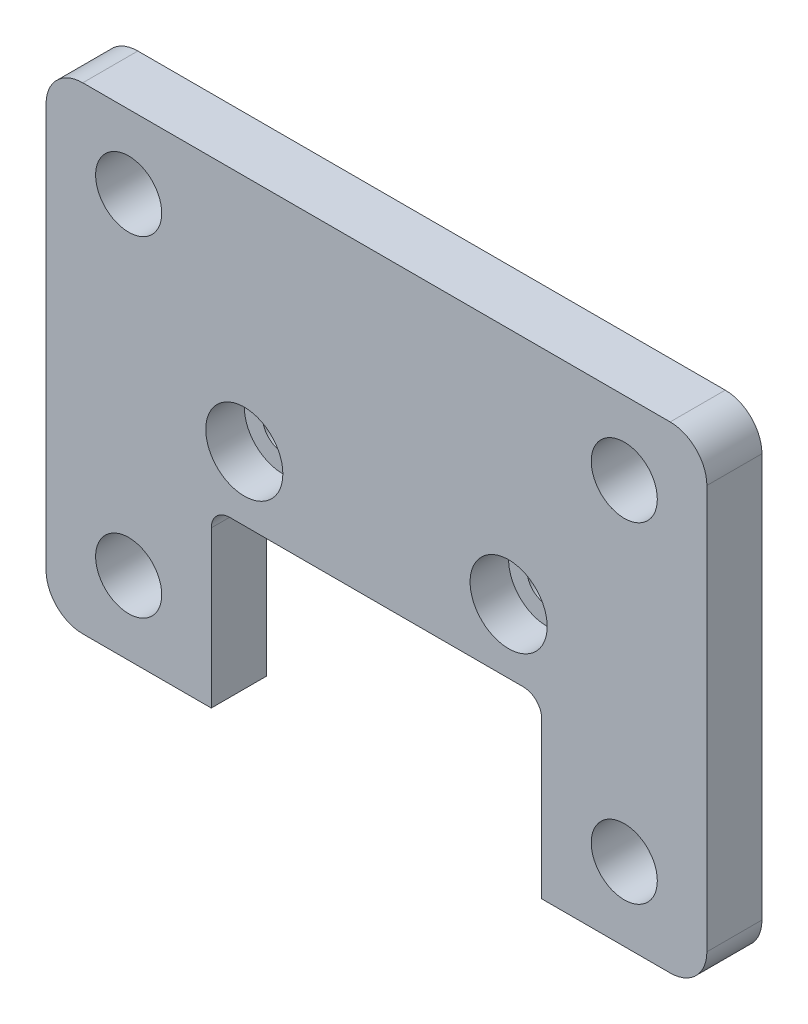
SolidWorks part; units mm, degrees
ref_plane "前视基准面" through (0, 0, 0) normal (0, 0, 1) x (1, 0, 0)
ref_plane "上视基准面" through (0, 0, 0) normal (0, 1, 0) x (1, 0, 0)
ref_plane "右视基准面" through (0, 0, 0) normal (1, 0, 0) x (0, 0, -1)
sketch "草图1" plane through (0, 0, 0) normal (0, 0, 1) x (1, 0, 0)
  line L0 (-16, -13) -> (16, -13)
  line L1 (18, -11) -> (18, 11)
  line L2 (16, 13) -> (-16, 13)
  line L3 (-18, 11) -> (-18, -11)
  arc A0 (16, -13) -> (18, -11) centre (16, -11) ccw
  arc A1 (18, 11) -> (16, 13) centre (16, 11) ccw
  arc A2 (-16, 13) -> (-18, 11) centre (-16, 11) ccw
  arc A3 (-18, -11) -> (-16, -13) centre (-16, -11) ccw
  dimension "D1" = 2
  dimension "D2" = 18
  dimension "D3" = 18
  dimension "D4" = 13
  dimension "D5" = 13
extrude "背板拉伸_厚3_前面Z5" add sketch "草图1" along normal blind 3 from offset 5
sketch "草图2" plane through (0, 0, 0) normal (0, 0, 1) x (1, 0, 0)
  line L0 (-8, -20) -> (8, -20)
  line L1 (9, -19) -> (9, -4.5)
  line L2 (8, -3.5) -> (-8, -3.5)
  line L3 (-9, -4.5) -> (-9, -19)
  arc A0 (8, -20) -> (9, -19) centre (8, -19) ccw
  arc A1 (9, -4.5) -> (8, -3.5) centre (8, -4.5) ccw
  arc A2 (-8, -3.5) -> (-9, -4.5) centre (-8, -4.5) ccw
  arc A3 (-9, -19) -> (-8, -20) centre (-8, -19) ccw
  dimension "D1" = 1
  dimension "D2" = 9
  dimension "D3" = 9
  dimension "D4" = 3.5
  dimension "D5" = 20
extrude "下方U口_宽18_向下敞开" cut sketch "草图2" along normal blind 3 from offset 5
sketch "草图3" plane through (0, 0, 0) normal (0, 0, 1) x (1, 0, 0)
  circle A0 centre (-7.2, 0) radius 2.75
  circle A1 centre (7.2, 0) radius 2.75
  dimension "D1" = 5.5
  dimension "D2" = 7.2
  dimension "D3" = 7.2
extrude "两根支柱主体_高2_Z3至5" add sketch "草图3" along normal blind 2 from offset 3
sketch "草图4" plane through (0, 0, 0) normal (0, 0, 1) x (1, 0, 0)
  circle A0 centre (-7.2, 0) radius 2
  circle A1 centre (7.2, 0) radius 2
  dimension "D1" = 4
  dimension "D2" = 7.2
  dimension "D3" = 7.2
extrude "两根接触细颈_高3_Z0至3" add sketch "草图4" along normal blind 3
sketch "草图5" plane through (0, 0, 0) normal (0, 0, 1) x (1, 0, 0)
  circle A0 centre (-7.2, 0) radius 1.1
  circle A1 centre (7.2, 0) radius 1.1
  dimension "D1" = 2.2
  dimension "D2" = 7.2
  dimension "D3" = 7.2
extrude "模块固定孔_2x直径2.2_贯穿" cut sketch "草图5" along normal blind 8
sketch "草图6" plane through (0, 0, 0) normal (0, 0, 1) x (1, 0, 0)
  circle A0 centre (-7.2, 0) radius 2.1
  circle A1 centre (7.2, 0) radius 2.1
  dimension "D1" = 4.2
  dimension "D2" = 7.2
  dimension "D3" = 7.2
extrude "背面螺丝头沉孔_深2.1" cut sketch "草图6" along normal blind 2.1 from offset 5.9
sketch "草图7" plane through (0, 0, 0) normal (0, 0, 1) x (1, 0, 0)
  circle A0 centre (-13.5, -9) radius 1.8
  circle A1 centre (-13.5, 9) radius 1.8
  circle A2 centre (13.5, -9) radius 1.8
  circle A3 centre (13.5, 9) radius 1.8
  dimension "D1" = 3.6
  dimension "D2" = 13.5
  dimension "D3" = 13.5
  dimension "D4" = 9
  dimension "D5" = 9
extrude "后续连接孔_4x直径3.6_贯穿" cut sketch "草图7" along normal blind 3 from offset 5
